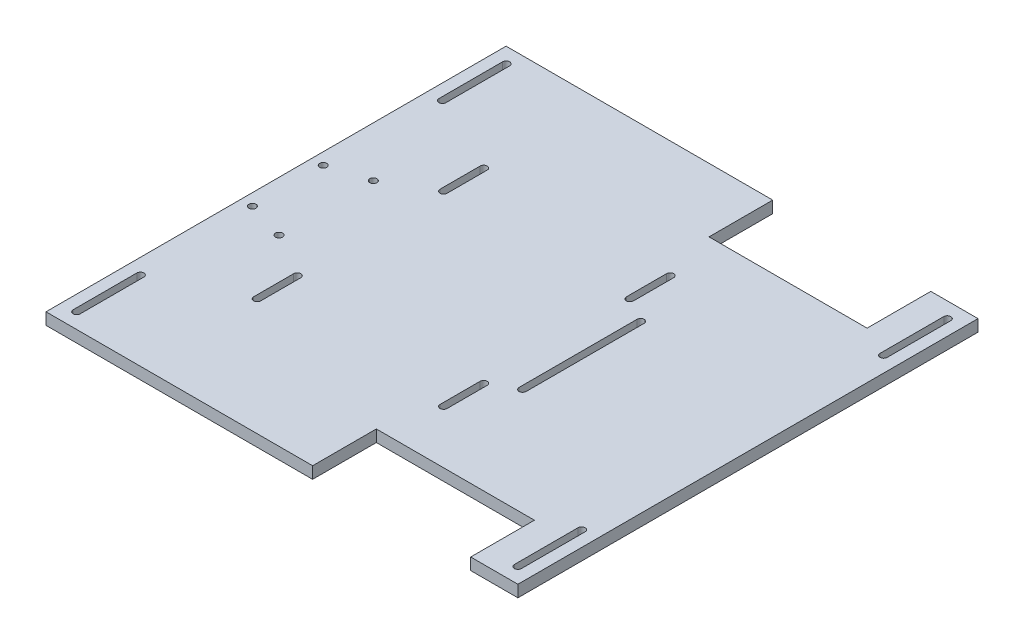
SolidWorks part; units mm, degrees
ref_plane "Front Plane" through (0, 0, 0) normal (0, 0, 1) x (1, 0, 0)
ref_plane "Top Plane" through (0, 0, 0) normal (0, 1, 0) x (1, 0, 0)
ref_plane "Right Plane" through (0, 0, 0) normal (1, 0, 0) x (0, 0, -1)
sketch "Sketch2" plane through (0, 0, 0) normal (0, 1, 0) x (1, 0, 0)
  line L1 (-100, -97.5) -> (100, -97.5)
  line L2 (-100, -97.5) -> (-100, 97.5)
  line L3 (-100, 97.5) -> (100, 97.5)
  line L4 (100, -97.5) -> (100, 97.5)
  line L5 (-100, -97.5) -> (100, 97.5) construction
  line L6 (-100, 97.5) -> (100, -97.5) construction
  point P0 (0, 0)
  dimension "D1" = 200
  dimension "D2" = 195
extrude "Boss-Extrude1" add sketch "Sketch2" along normal blind 5
sketch "Sketch3" plane through (0, 5, 0) normal (0, 1, 0) x (1, 0, 0)
  line L0 (-100, 0) -> (100, 0) construction
  line L1 (-100, 97.5) -> (-100, -97.5) construction
  line L2 (100, -97.5) -> (100, 97.5) construction
  line L3 (0, -97.5) -> (0, 97.5) construction
  line L4 (-100, -97.5) -> (100, -97.5) construction
  line L5 (100, 97.5) -> (-100, 97.5) construction
  line L6 (-93.5, -91) -> (-93.5, -64) construction
  line L7 (-95, -91) -> (-95, -64)
  line L8 (-92, -91) -> (-92, -64)
  line L9 (-93.5, 91) -> (-93.5, 64) construction
  line L10 (-95, 91) -> (-95, 64)
  line L11 (-92, 91) -> (-92, 64)
  line L12 (93.5, 91) -> (93.5, 64) construction
  line L13 (95, 91) -> (95, 64)
  line L14 (92, 91) -> (92, 64)
  line L15 (93.5, -91) -> (93.5, -64) construction
  line L16 (95, -91) -> (95, -64)
  line L17 (92, -91) -> (92, -64)
  arc A0 (-95, -91) -> (-92, -91) centre (-93.5, -91) ccw
  arc A1 (-92, -64) -> (-95, -64) centre (-93.5, -64) ccw
  arc A2 (-95, 91) -> (-92, 91) centre (-93.5, 91) cw
  arc A3 (-92, 64) -> (-95, 64) centre (-93.5, 64) cw
  arc A4 (95, 91) -> (92, 91) centre (93.5, 91) ccw
  arc A5 (92, 64) -> (95, 64) centre (93.5, 64) ccw
  arc A6 (95, -91) -> (92, -91) centre (93.5, -91) cw
  arc A7 (92, -64) -> (95, -64) centre (93.5, -64) cw
  point P14 (-93.5, -77.5)
  point P21 (-93.5, 77.5)
  point P28 (93.5, 77.5)
  point P35 (93.5, -77.5)
  dimension "D2" = 1.5
  dimension "D3" = 5
  dimension "D4" = 6.5
  dimension "D1" = 27
extrude "Cut-Extrude1" cut sketch "Sketch3" against normal through all
sketch "Sketch4" plane through (0, 0, 0) normal (0, -1, 0) x (1, 0, 0)
  line L0 (-100, 0) -> (100, 0) construction
  line L1 (-100, -97.5) -> (-100, 97.5) construction
  line L2 (100, 97.5) -> (100, -97.5) construction
  line L3 (100, -97.5) -> (-100, -97.5) construction
  line L4 (13, -97.5) -> (80, -97.5)
  line L5 (13, -97.5) -> (13, -70.5)
  line L6 (13, -70.5) -> (80, -70.5)
  line L7 (80, -97.5) -> (80, -70.5)
  line L8 (80, 97.5) -> (80, 70.5)
  line L9 (13, 97.5) -> (80, 97.5)
  line L10 (13, 70.5) -> (80, 70.5)
  line L11 (13, 97.5) -> (13, 70.5)
  dimension "D1" = 27
  dimension "D2" = 67
  dimension "D3" = 20
extrude "Cut-Extrude2" cut sketch "Sketch4" against normal through all
sketch "Sketch5" plane through (0, 0, 0) normal (0, -1, 0) x (1, 0, 0)
  line L0 (-100, 0) -> (100, 0) construction
  line L1 (-100, -97.5) -> (-100, 97.5) construction
  line L2 (100, 97.5) -> (100, -97.5) construction
  line L3 (13, -70.5) -> (13, -97.5) construction
  line L4 (23, -52) -> (-64, -52)
  line L5 (23, -52) -> (23, 52)
  line L6 (23, 52) -> (-64, 52)
  line L7 (-64, -52) -> (-64, 52)
  line L8 (23, -52) -> (-64, 52) construction
  line L9 (23, 52) -> (-64, -52) construction
  line L10 (-60, -48) -> (-60, -31) construction
  line L11 (-61.5, -48) -> (-61.5, -31)
  line L12 (-58.5, -48) -> (-58.5, -31)
  line L13 (-60, 48) -> (-60, 31) construction
  line L14 (-61.5, 48) -> (-61.5, 31)
  line L15 (-58.5, 48) -> (-58.5, 31)
  line L16 (-20.5, -52) -> (-20.5, 52) construction
  line L17 (19, 48) -> (19, 31) construction
  line L18 (20.5, 48) -> (20.5, 31)
  line L19 (17.5, 48) -> (17.5, 31)
  line L20 (19, -48) -> (19, -31) construction
  line L21 (20.5, -48) -> (20.5, -31)
  line L22 (17.5, -48) -> (17.5, -31)
  arc A0 (-61.5, -48) -> (-58.5, -48) centre (-60, -48) ccw
  arc A1 (-58.5, -31) -> (-61.5, -31) centre (-60, -31) ccw
  arc A2 (-61.5, 48) -> (-58.5, 48) centre (-60, 48) cw
  arc A3 (-58.5, 31) -> (-61.5, 31) centre (-60, 31) cw
  arc A4 (20.5, 48) -> (17.5, 48) centre (19, 48) ccw
  arc A5 (17.5, 31) -> (20.5, 31) centre (19, 31) ccw
  arc A6 (20.5, -48) -> (17.5, -48) centre (19, -48) cw
  arc A7 (17.5, -31) -> (20.5, -31) centre (19, -31) cw
  point P6 (-20.5, 0)
  point P15 (-60, -39.5)
  point P22 (-60, 39.5)
  point P31 (19, 39.5)
  point P38 (19, -39.5)
  dimension "D5" = 1.5
  dimension "D1" = 104
  dimension "D2" = 87
  dimension "D3" = 10
  dimension "D4" = 17
  dimension "D6" = 2.5
  dimension "D7" = 4
extrude "Cut-Extrude4" cut sketch "Sketch5" against normal through all contours L11 A1 L12 A0 | L14 A3 L15 A2 | L19 A5 L18 A4 | L22 A7 L21 A6
sketch "Sketch7" plane through (0, 0, 0) normal (0, -1, 0) x (1, 0, 0)
  line L0 (29.5, -25) -> (29.5, 25) construction
  line L1 (-100, 0) -> (100, 0) construction
  line L2 (28, -25) -> (28, 25)
  line L3 (31, -25) -> (31, 25)
  line L4 (23, -52) -> (23, 52) construction
  arc A0 (28, -25) -> (31, -25) centre (29.5, -25) ccw
  arc A1 (31, 25) -> (28, 25) centre (29.5, 25) ccw
  point P4 (29.5, 0)
  dimension "D2" = 1.5
  dimension "D1" = 50
  dimension "D3" = 5
extrude "Cut-Extrude5" cut sketch "Sketch7" against normal through all
sketch "Sketch8" plane through (0, 5, 0) normal (0, 1, 0) x (1, 0, 0)
  line L0 (-100, 0) -> (100, 0) construction
  line L1 (-100, 97.5) -> (-100, -97.5) construction
  line L2 (100, -97.5) -> (100, 97.5) construction
  line L3 (-78.75, -25) -> (-78.75, 25) construction
  line L4 (-95, -25) -> (-62.5, -25)
  line L5 (-95, -25) -> (-95, 25)
  line L6 (-95, 25) -> (-62.5, 25)
  line L7 (-62.5, -25) -> (-62.5, 25)
  line L8 (-95, -25) -> (-62.5, 25) construction
  line L9 (-95, 25) -> (-62.5, -25) construction
  circle A0 centre (-78.75, -19.995) radius 1.5
  circle A1 centre (-78.75, 19.995) radius 1.5
  point P6 (-78.75, 0)
  dimension "D4" = 3
  dimension "D1" = 32.5
  dimension "D2" = 50
  dimension "D3" = 5
  dimension "D5" = 39.99
extrude "Cut-Extrude6" cut sketch "Sketch8" against normal through all contours A1 | A0
sketch "Sketch9" plane through (0, 5, 0) normal (0, 1, 0) x (1, 0, 0)
  line L0 (-100, 0) -> (100, 0) construction
  line L1 (-100, 97.5) -> (-100, -97.5) construction
  line L2 (100, -97.5) -> (100, 97.5) construction
  line L4 (-100, -25) -> (-90, -25)
  line L5 (-100, -25) -> (-100, 25)
  line L6 (-100, 25) -> (-90, 25)
  line L7 (-90, -25) -> (-90, 25)
  line L8 (-100, -25) -> (-90, 25) construction
  line L9 (-100, 25) -> (-90, -25) construction
  circle A0 centre (-95, 15) radius 1.5
  circle A1 centre (-95, -15) radius 1.5
  point P6 (-95, 0)
  dimension "D4" = 3
  dimension "D1" = 10
  dimension "D2" = 0
  dimension "D3" = 50
  dimension "D5" = 30
  dimension "D6" = 5
extrude "Cut-Extrude7" cut sketch "Sketch9" against normal through all contours A0 | A1
